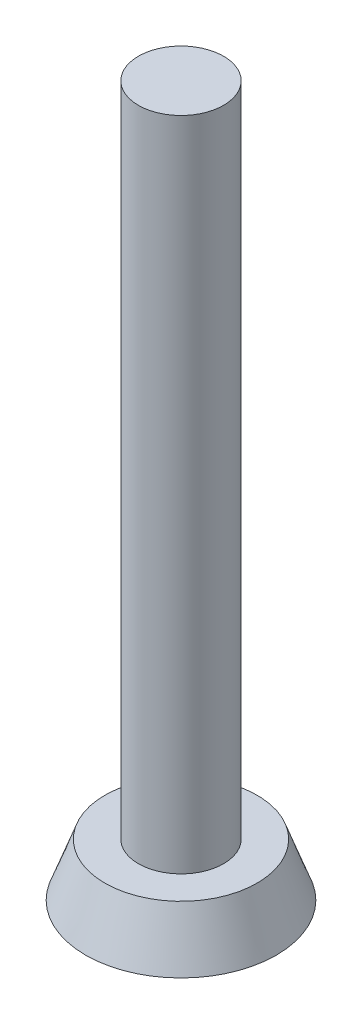
SolidWorks part; units mm, degrees
ref_plane "Front Plane" through (0, 0, 0) normal (0, 0, 1) x (1, 0, 0)
ref_plane "Top Plane" through (0, 0, 0) normal (0, 1, 0) x (1, 0, 0)
ref_plane "Right Plane" through (0, 0, 0) normal (1, 0, 0) x (0, 0, -1)
sketch "Sketch1" plane through (0, 0, 0) normal (0, 1, 0) x (1, 0, 0)
  circle A0 centre (0, 0) radius 3.36
  dimension "D1" = 6.72
extrude "Boss-Extrude1" add sketch "Sketch1" along normal blind 1.86 draft 20
sketch "Sketch2" plane through (0, 1.86, 0) normal (0, 1, 0) x (1, 0, 0)
  circle A0 centre (0, 0) radius 1.5
  dimension "D1" = 3
extrude "Boss-Extrude2" add sketch "Sketch2" along normal blind 23.14
sketch "Sketch3" plane through (0, 0, 0) normal (0, -1, 0) x (1, 0, 0)
  line L1 (0, 1.1547) -> (-1, 0.5774)
  line L2 (-1, 0.5774) -> (-1, -0.5774)
  line L3 (-1, -0.5774) -> (0, -1.1547)
  line L4 (0, -1.1547) -> (1, -0.5774)
  line L5 (1, -0.5774) -> (1, 0.5774)
  line L6 (1, 0.5774) -> (0, 1.1547)
  circle A0 centre (0, 0) radius 1 construction
  dimension "D1" = 2
extrude "Cut-Extrude1" cut sketch "Sketch3" against normal blind 1.5
